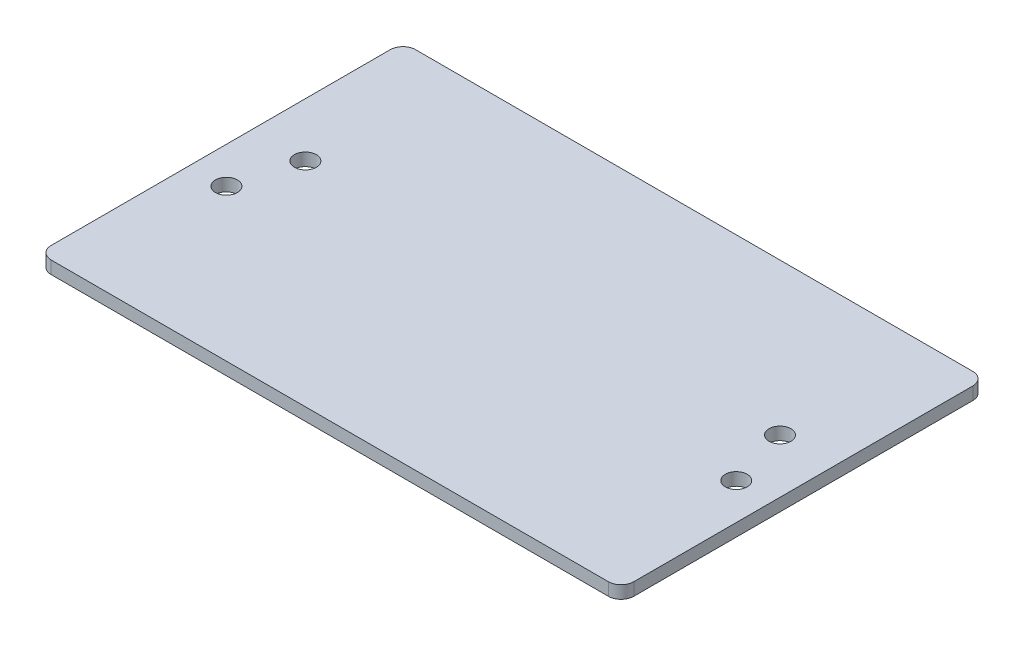
SolidWorks part; units mm, degrees
material "6061 Alloy"
ref_plane "Front Plane" through (0, 0, 0) normal (0, 0, 1) x (1, 0, 0)
ref_plane "Top Plane" through (0, 0, 0) normal (0, 1, 0) x (1, 0, 0)
ref_plane "Right Plane" through (0, 0, 0) normal (1, 0, 0) x (0, 0, -1)
ref_plane "Plane1" through (0, 0, 0) normal (0, 1, 0) x (1, 0, 0)
sketch "Sketch1" plane through (0, 0, 0) normal (0, 1, 0) x (1, 0, 0)
  line L0 (73.025, 0) -> (73.025, 91.35) construction
  line L1 (0, 0) -> (146.05, 0)
  line L2 (0, 0) -> (0, 91.35)
  line L3 (0, 91.35) -> (146.05, 91.35)
  line L4 (146.05, 0) -> (146.05, 91.35)
  circle A0 centre (13.525, 53.3651) radius 2.75
  circle A1 centre (9.1148, 37.9849) radius 2.75
  circle A2 centre (132.525, 53.3651) radius 2.75
  circle A3 centre (136.9352, 37.9849) radius 2.75
  point P5 (13.525, 53.3651)
  point P6 (9.1148, 37.9849)
  point P9 (136.9352, 37.9849)
  point P11 (132.525, 53.3651)
  dimension "D12" = 5.5
  dimension "D13" = 5.5
  dimension "D14" = 5.5
  dimension "D15" = 5.5
  dimension "D1" = 91.35
  dimension "D2" = 146.05
  dimension "D3" = 4.4102
  dimension "D4" = 15.3802
  dimension "D5" = 16
  dimension "D6" = 4.4102
  dimension "D7" = 15.3802
  dimension "D8" = 119
  dimension "D9" = 37.9849
  dimension "D10" = 37.9849
  dimension "D11" = 73.025
extrude "Boss-Extrude1" add sketch "Sketch1" along normal blind 3.175
ref_plane "Plane2" through (0, 3.175, 0) normal (0, 1, 0) x (1, 0, 0)
sketch "Sketch2" plane through (0, 3.175, 0) normal (0, 1, 0) x (1, 0, 0)
  line L0 (0, 0) -> (146.05, 0) construction
  line L1 (0, 91.35) -> (0, 0) construction
  circle A0 centre (15, 15) radius 2
  dimension "D3" = 4
  dimension "D1" = 15
  dimension "D2" = 15
extrude "Cut-Extrude1" [suppressed] cut sketch "Sketch2" against normal through all
fillet "Fillet1" radius 3.175 4 edges at (0, 1.5875, 0) (146.05, 1.5875, 0) (146.05, 1.5875, -91.35) (0, 1.5875, -91.35)
